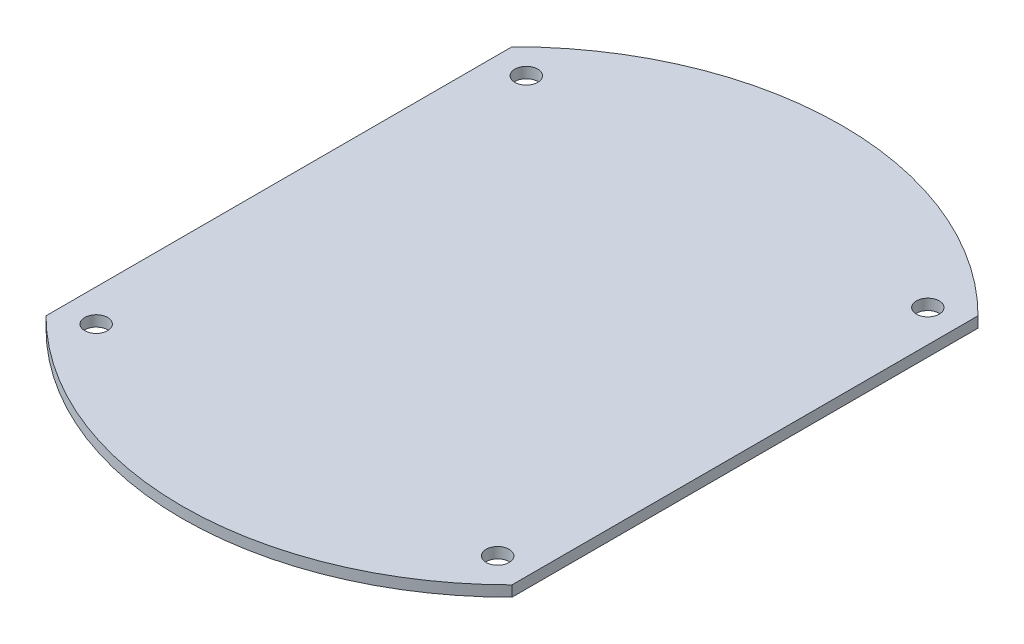
SolidWorks part; units mm, degrees
ref_plane "Спереди" through (0, 0, 0) normal (0, 0, 1) x (1, 0, 0)
ref_plane "Сверху" through (0, 0, 0) normal (0, 1, 0) x (1, 0, 0)
ref_plane "Справа" through (0, 0, 0) normal (1, 0, 0) x (0, 0, -1)
sketch "Эскиз1" plane through (0, 0, 0) normal (0, 1, 0) x (1, 0, 0)
  line L0 (0, -1000) -> (0, 49000) construction
  line L1 (-32.5, -32.5) -> (32.5, -32.5)
  line L2 (-32.5, -32.5) -> (-32.5, 32.5)
  line L3 (-32.5, 32.5) -> (32.5, 32.5)
  line L4 (32.5, -32.5) -> (32.5, 32.5)
  line L5 (-32.5, -32.5) -> (32.5, 32.5) construction
  line L6 (-32.5, 32.5) -> (32.5, -32.5) construction
  line L7 (-1000, 0) -> (49000, 0) construction
  arc A0 (-32.5, 32.5) -> (32.5, 32.5) centre (0, 0.1296) cw
  arc A1 (-32.5, -32.5) -> (32.5, -32.5) centre (0, -0.1296) ccw
  circle A2 centre (28, 30) radius 1.6
  circle A3 centre (-28, 30) radius 1.6
  circle A4 centre (28, -30) radius 1.6
  circle A5 centre (-28, -30) radius 1.6
  point P0 (0, 0)
  point P10 (0, 46)
  point P13 (0, -46)
  dimension "D3" = 3.2
  dimension "D1" = 65
  dimension "D2" = 92
  dimension "D4" = 56
  dimension "D5" = 60
extrude "Бобышка-Вытянуть1" add sketch "Эскиз1" along normal blind 1.5 contours L1 A1 | L1 L4 L3 L2 A5 A3 A2 A4 | A0 L3
